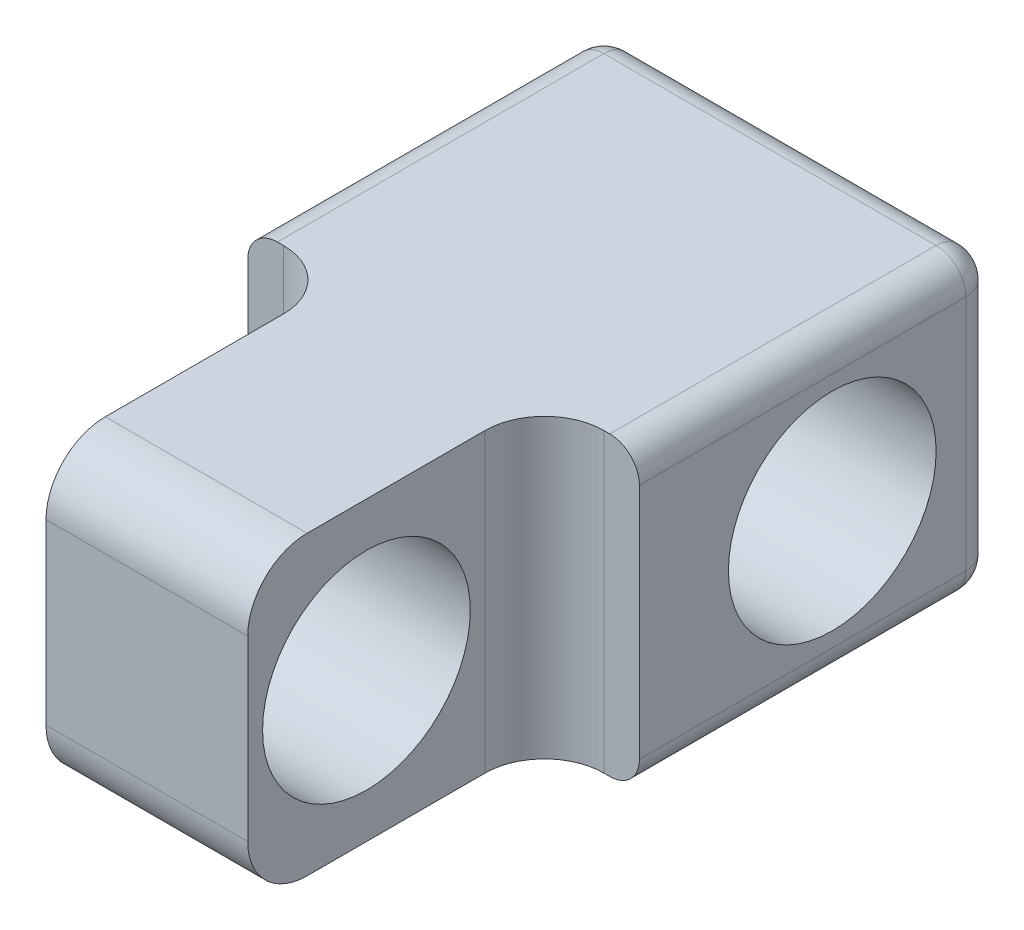
SolidWorks part; units mm, degrees
ref_plane "Front Plane" through (0, 0, 0) normal (0, 0, 1) x (1, 0, 0)
ref_plane "Top Plane" through (0, 0, 0) normal (0, 1, 0) x (1, 0, 0)
ref_plane "Right Plane" through (0, 0, 0) normal (1, 0, 0) x (0, 0, -1)
sketch "Sketch1" plane through (0, 0, 0) normal (0, 0, 1) x (1, 0, 0)
  line L1 (0.5, 0) -> (6.1, 0)
  line L2 (0, 0.5) -> (0, 4.5)
  line L3 (0.5, 5) -> (6.1, 5)
  line L4 (6.6, 0.5) -> (6.6, 4.5)
  arc A0 (6.1, 5) -> (6.6, 4.5) centre (6.1, 4.5) cw
  arc A1 (6.6, 0.5) -> (6.1, 0) centre (6.1, 0.5) cw
  arc A2 (0.5, 0) -> (0, 0.5) centre (0.5, 0.5) cw
  arc A3 (0.5, 5) -> (0, 4.5) centre (0.5, 4.5) ccw
  point P9 (6.6, 0)
  point P12 (0, 0)
  point P15 (0, 5)
  dimension "D3" = 0.5
  dimension "D1" = 6.6
  dimension "D2" = 5
extrude "Boss-Extrude1" add sketch "Sketch1" along normal blind 6
sketch "Sketch2" plane through (6.6, 0, 0) normal (1, 0, 0) x (0, 0, -1)
  circle A0 centre (-2.75, 2.5) radius 1.75
  dimension "D1" = 3.5
extrude "Cut-Extrude1" cut sketch "Sketch2" against normal blind 6.6
fillet "Fillet1" radius 0.5 8 edges at (6.4536, 4.8536, 0) (6.6, 2.5, 0) (6.4536, 0.1464, 0) (3.3, 0, 0) (0.1464, 0.1464, 0) (0, 2.5, 0) (0.1464, 4.8536, 0) (3.3, 5, 0)
sketch "Sketch3" plane through (0, 0, 6) normal (0, 0, 1) x (1, 0, 0)
  line L1 (6.1, 5) -> (0.5, 5) construction
  line L2 (5, 5) -> (5, 0)
  line L3 (0.5, 0) -> (6.1, 0) construction
  line L4 (5, 0) -> (1.6, 0)
  line L5 (1.6, 0) -> (1.6, 5)
  line L7 (1.6, 5) -> (5, 5)
extrude "Boss-Extrude2" add sketch "Sketch3" along normal blind 5
fillet "Fillet2" radius 1 2 edges at (5, 2.5, 6) (1.6, 2.5, 6)
sketch "Sketch5" plane through (5, 0, 0) normal (1, 0, 0) x (0, 0, -1)
  circle A0 centre (-9, 2.5) radius 1.75
  dimension "D1" = 3.5
extrude "Cut-Extrude2" cut sketch "Sketch5" against normal blind 4
fillet "Fillet3" radius 1 2 edges at (3.3, 0, 11) (3.3, 5, 11)
